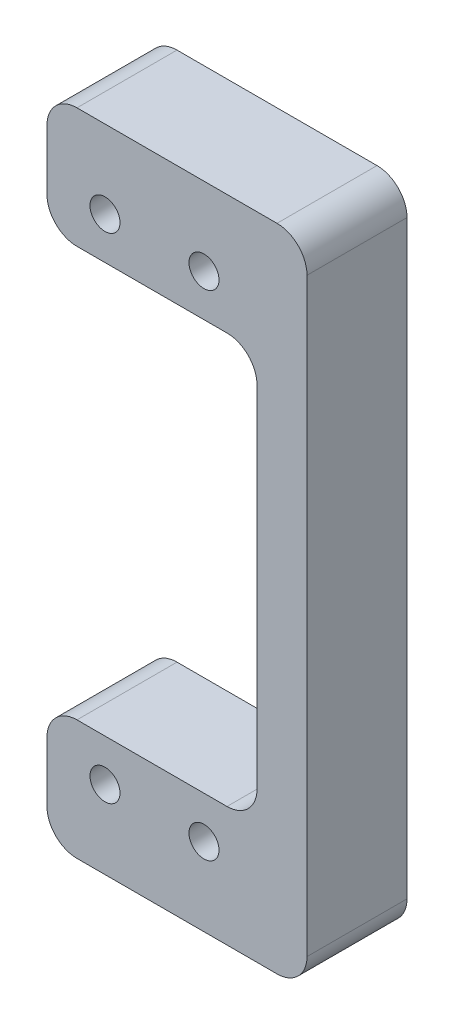
SolidWorks part; units mm, degrees
ref_plane "Front Plane" through (0, 0, 0) normal (0, 0, 1) x (1, 0, 0)
ref_plane "Top Plane" through (0, 0, 0) normal (0, 1, 0) x (1, 0, 0)
ref_plane "Right Plane" through (0, 0, 0) normal (1, 0, 0) x (0, 0, -1)
sketch "Sketch1" plane through (0, 0, 0) normal (0, 0, 1) x (1, 0, 0)
  line L0 (0, -20.5) -> (0, 20.5)
  line L1 (0, 20.5) -> (-21, 20.5)
  line L2 (-21, 20.5) -> (-21, 32.5)
  line L3 (-21, 32.5) -> (5, 32.5)
  line L4 (5, 32.5) -> (5, -32.5)
  line L5 (5, -32.5) -> (-21, -32.5)
  line L6 (-21, -32.5) -> (-21, -20.5)
  line L7 (-21, -20.5) -> (0, -20.5)
  dimension "D1" = 12
  dimension "D2" = 41
  dimension "D3" = 21
  dimension "D4" = 5
extrude "Boss-Extrude1" add sketch "Sketch1" along normal blind 10
fillet "Fillet1" radius 3 8 edges at (5, -32.5, 5) (-21, -32.5, 5) (-21, -20.5, 5) (0, -20.5, 5) (0, 20.5, 5) (-21, 20.5, 5) (-21, 32.5, 5) (5, 32.5, 5)
hole_wizard "Ø3.0mm Dowel Hole1" positions "Sketch2" profile "Sketch3" hole size "Ø3.0" standard "ISO" end condition through all
sketch "Sketch2" plane through (0, 0, 10) normal (0, 0, 1) x (1, 0, 0)
  line L1 (0, 17.5) -> (0, -17.5) construction
  point P0 (-5.3, 24.695)
  point P2 (-15.2, 24.695)
  point P15 (0, 0)
  point P16 (0, 0)
  point P17 (0, 0)
  dimension "D1" = 9.9
  dimension "D2" = 5.3
  dimension "D3" = 24.695
sketch "Sketch3" plane through (-5.3, 24.695, 10) normal (1, 0, 0) x (0, -1, 0)
  line L0 (0, 0) -> (0, 10)
  line L1 (0, 10) -> (1.5, 10)
  line L2 (1.5, 10) -> (1.5, 0)
  line L5 (1.5, 0) -> (0, 0)
  line L11 (0, -6.35) -> (0, 107.95) construction
  dimension "Thru Hole Dia." = 3
  dimension "Thru Hole Depth" = 10
mirror "Mirror1" about plane through (0, 0, 0) normal (0, 1, 0) of "Ø3.0mm Dowel Hole1"
